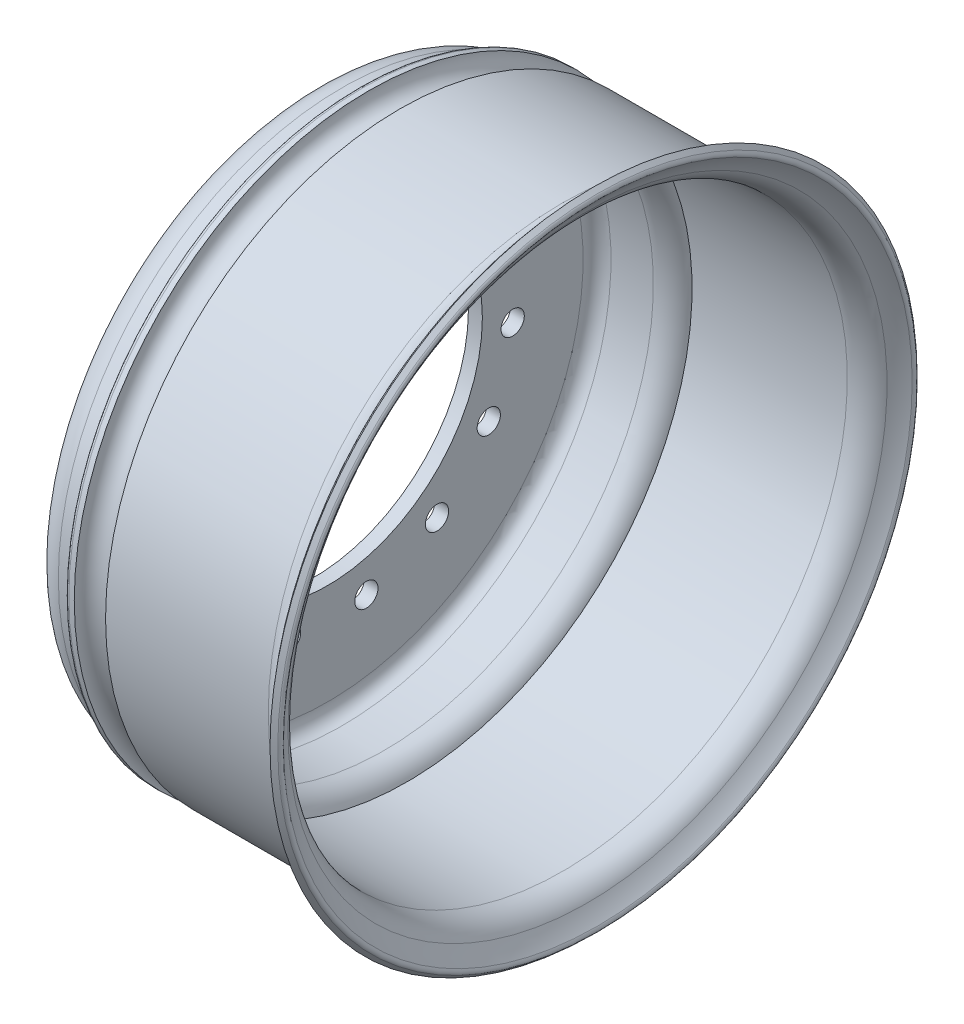
SolidWorks part; units mm, degrees
ref_plane "Front Plane" through (0, 0, 0) normal (0, 0, 1) x (1, 0, 0)
ref_plane "Top Plane" through (0, 0, 0) normal (0, 1, 0) x (1, 0, 0)
ref_plane "Right Plane" through (0, 0, 0) normal (1, 0, 0) x (0, 0, -1)
sketch "Sketch1" plane through (0, 0, 0) normal (0, 0, 1) x (1, 0, 0)
  line L0 (0, 75.6292) -> (0, 0) construction
  line L1 (0, 0) -> (74.7031, 0) construction
  line L2 (0, 190) -> (6, 190)
  line L3 (25.998, 189.7996) -> (130.998, 189.7996)
  line L4 (0, 184) -> (1.0861, 184)
  line L5 (30.8304, 183.7996) -> (130.998, 183.7996)
  line L6 (155.3986, 204.6212) -> (151, 208.7019)
  line L7 (15.8902, 173.8) -> (-11.4681, 173.8)
  line L8 (-20.4681, 164.8) -> (-20.4681, 99.8)
  line L9 (-20.4681, 99.8) -> (-29.4681, 99.8)
  line L10 (-29.4681, 99.8) -> (-29.4681, 164.8)
  line L11 (-11.4681, 182.8) -> (1.6103, 182.8)
  line L12 (0, 190) -> (0, 184)
  arc A0 (6, 190) -> (25.998, 189.7996) centre (15.998, 189.7996) ccw
  arc A1 (130.998, 189.7996) -> (141.9098, 196.2019) centre (130.998, 202.2996) ccw
  arc A2 (141.9098, 196.2019) -> (151, 208.7019) centre (198.6514, 164.4939) cw
  arc A3 (1.0861, 184) -> (1.6103, 182.8) centre (15.998, 189.7996) ccw
  arc A4 (130.998, 183.7996) -> (147.1475, 193.275) centre (130.998, 202.2996) ccw
  arc A5 (147.1475, 193.275) -> (155.3986, 204.6212) centre (198.6514, 164.4939) cw
  arc A6 (-11.4681, 173.8) -> (-20.4681, 164.8) centre (-11.4681, 164.8) ccw
  arc A7 (-29.4681, 164.8) -> (-11.4681, 182.8) centre (-11.4681, 164.8) cw
  arc A8 (15.8902, 173.8) -> (30.8304, 183.7996) centre (15.998, 189.7996) ccw
  arc A10 (1.0861, 184) -> (30.8304, 183.7996) centre (15.998, 189.7996) ccw construction
  dimension "D3" = 10
  dimension "D4" = 12.5
  dimension "D6" = 145
  dimension "D5" = 65
  dimension "D10" = 9
  dimension "D11" = 18
  dimension "D1" = 105
  dimension "D2" = 6
  dimension "D7" = 12.5
  dimension "D8" = 190
  dimension "D9" = 6
  dimension "D12" = 9
  dimension "D13" = 9
  dimension "D14" = 65
revolve "Revolve1" add sketch "Sketch1" angle 360 about L1
sketch "Sketch2" plane through (-29.4681, 0, 0) normal (-1, 0, 0) x (0, 0, 1)
  circle A0 centre (0, 120) radius 7.5
  point P2 (0, 0)
  dimension "D1" = 15
  dimension "D2" = 120
extrude "Cut-Extrude1" cut sketch "Sketch2" against normal through all
pattern_circular "CirPattern1" count 15 over 360 about axis through (0, 0, 0) along (1, 0, 0) of "Cut-Extrude1"
fillet "Fillet1" radius 2.5 2 edges at (155.3986, 0, 204.6212) (0, 0, 190)
